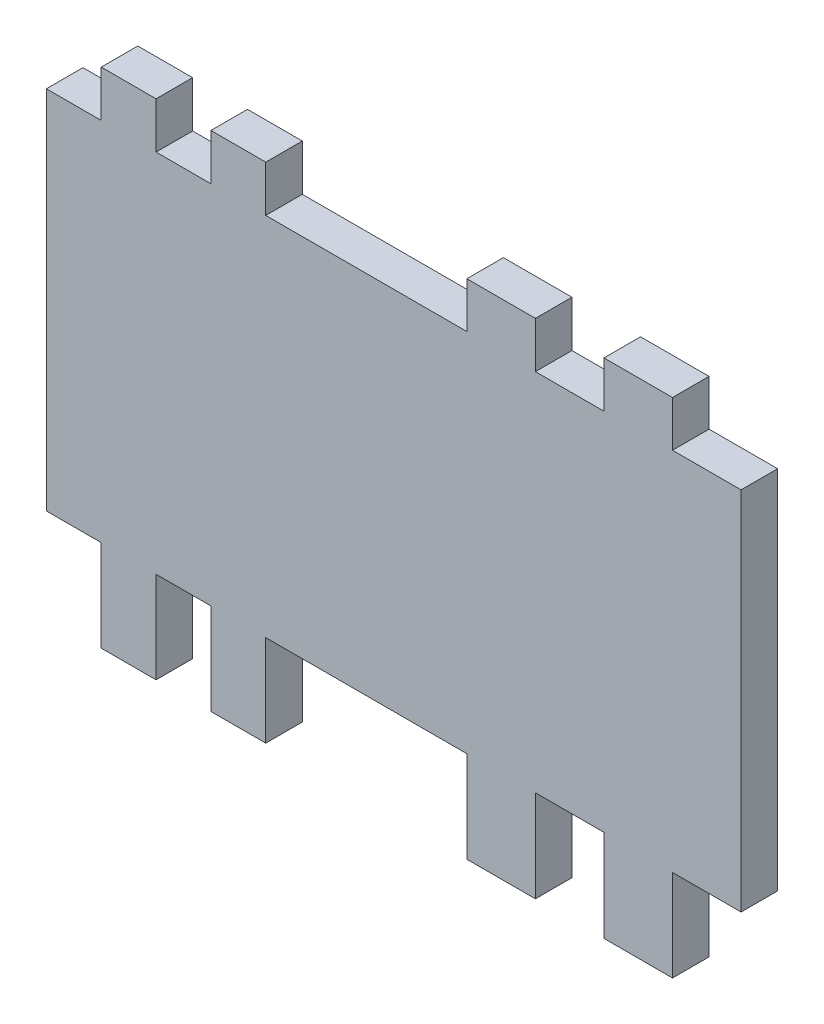
SolidWorks part; units mm, degrees
ref_plane "Front Plane" through (0, 0, 0) normal (0, 0, 1) x (1, 0, 0)
ref_plane "Top Plane" through (0, 0, 0) normal (0, 1, 0) x (1, 0, 0)
ref_plane "Right Plane" through (0, 0, 0) normal (1, 0, 0) x (0, 0, -1)
sketch "Sketch1" plane through (0, 0, 0) normal (0, 0, 1) x (1, 0, 0)
  line L0 (26.9898, 13.5459) -> (19.4898, 13.5459)
  line L1 (19.4898, 13.5459) -> (19.4898, 18.5459)
  line L2 (19.4898, 18.5459) -> (11.9898, 18.5459)
  line L3 (11.9898, 18.5459) -> (11.9898, 13.4949)
  line L4 (11.9898, 13.4949) -> (4.4898, 13.4949)
  line L5 (4.4898, 13.4949) -> (4.4898, 18.5459)
  line L6 (4.4898, 18.5459) -> (-3.0102, 18.5459)
  line L7 (-3.0102, 18.5459) -> (-3.0102, 13.5459)
  line L8 (-3.0102, 13.5459) -> (-25.0102, 13.5459)
  line L9 (-25.0102, 13.5459) -> (-25.0102, 18.5969)
  line L10 (-25.0102, 18.5969) -> (-31.0102, 18.5969)
  line L11 (-31.0102, 18.5969) -> (-31.0102, 13.5459)
  line L12 (-31.0102, 13.5459) -> (-37.0102, 13.5459)
  line L13 (-37.0102, 13.5459) -> (-37.0102, 18.5969)
  line L14 (-37.0102, 18.5969) -> (-43.0102, 18.5969)
  line L15 (-43.0102, 18.5969) -> (-43.0102, 13.5459)
  line L16 (-43.0102, 13.5459) -> (-49.0102, 13.5459)
  line L17 (26.9898, 13.5459) -> (26.9898, -26.4541)
  line L18 (-49.0102, 13.5459) -> (-49.0102, -26.4541)
  line L19 (-68.1122, -6.4541) -> (67.8061, -6.4541) construction
  line L20 (-31.0102, -31.5051) -> (-31.0102, -26.4541)
  line L21 (-43.0102, -26.4541) -> (-49.0102, -26.4541)
  line L22 (-43.0102, -31.5051) -> (-43.0102, -26.4541)
  line L23 (11.9898, -36.4541) -> (19.4898, -36.4541)
  line L24 (-37.0102, -26.4541) -> (-37.0102, -31.5051)
  line L25 (-31.0102, -26.4541) -> (-37.0102, -26.4541)
  line L26 (4.4898, -36.4541) -> (-3.0102, -36.4541)
  line L27 (-25.0102, -26.4541) -> (-25.0102, -31.5051)
  line L28 (-3.0102, -26.4541) -> (-25.0102, -26.4541)
  line L29 (-3.0102, -31.4541) -> (-3.0102, -26.4541)
  line L30 (-25.0102, -36.4541) -> (-31.0102, -36.4541)
  line L31 (4.4898, -26.4031) -> (4.4898, -31.4541)
  line L32 (11.9898, -26.4031) -> (4.4898, -26.4031)
  line L33 (11.9898, -31.4541) -> (11.9898, -26.4031)
  line L34 (19.4898, -26.4541) -> (19.4898, -31.4541)
  line L35 (-37.0102, -36.4541) -> (-43.0102, -36.4541)
  line L36 (26.9898, -26.4541) -> (19.4898, -26.4541)
  line L38 (19.4898, -31.4541) -> (19.4898, -36.4541)
  line L40 (11.9898, -36.4541) -> (11.9898, -31.4541)
  line L41 (4.4898, -31.4541) -> (4.4898, -36.4541)
  line L44 (-3.0102, -36.4541) -> (-3.0102, -31.4541)
  line L45 (-25.0102, -31.5051) -> (-25.0102, -36.4541)
  line L47 (-31.0102, -36.4541) -> (-31.0102, -31.5051)
  line L49 (-37.0102, -31.5051) -> (-37.0102, -36.4541)
  line L51 (-43.0102, -31.5051) -> (-43.0102, -36.4541)
  dimension "D1" = 7.5
  dimension "D2" = 7.5
  dimension "D3" = 7.5
  dimension "D4" = 7.5
  dimension "D5" = 6
  dimension "D6" = 6
  dimension "D7" = 6
  dimension "D8" = 6
  dimension "D9" = 76
  dimension "D10" = 5
  dimension "D11" = 40
extrude "Boss-Extrude1" add sketch "Sketch1" along normal blind 4
